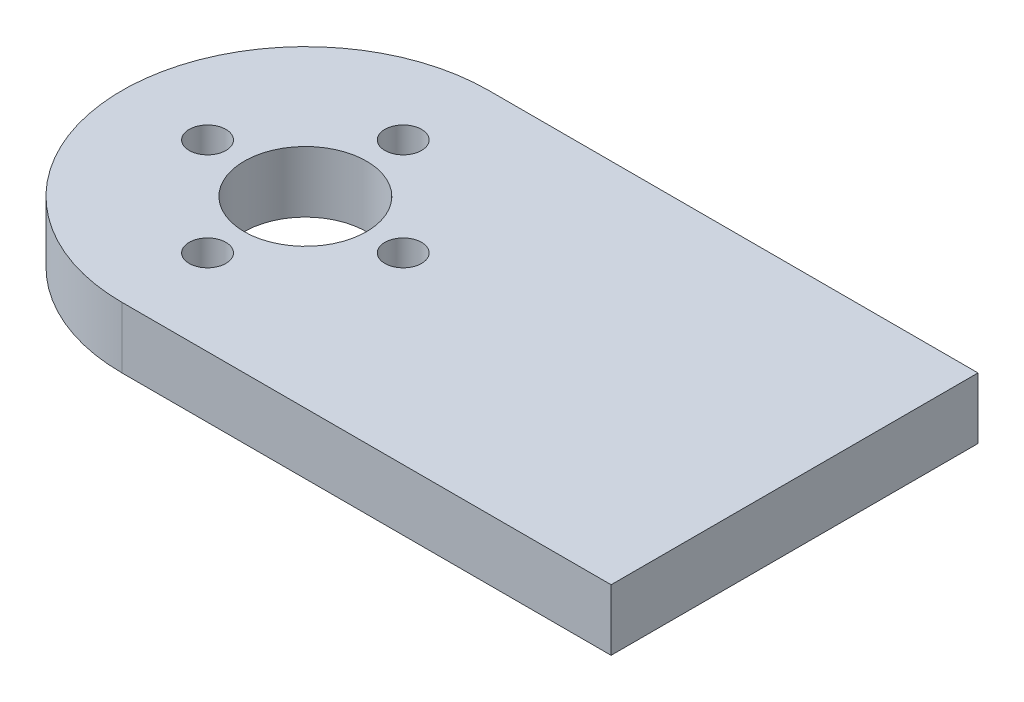
SolidWorks part; units mm, degrees
ref_plane "Front Plane" through (0, 0, 0) normal (0, 0, 1) x (1, 0, 0)
ref_plane "Top Plane" through (0, 0, 0) normal (0, 1, 0) x (1, 0, 0)
ref_plane "Right Plane" through (0, 0, 0) normal (1, 0, 0) x (0, 0, -1)
sketch "Sketch1" plane through (0, 0, 0) normal (0, 1, 0) x (1, 0, 0)
  line L0 (0, 0) -> (0, 8)
  line L2 (0, 15) -> (40, 15)
  line L3 (0, 15) -> (0, -15)
  line L4 (0, -15) -> (40, -15)
  line L5 (40, 15) -> (40, -15)
  circle A0 centre (0, 0) radius 5
  circle A1 centre (0, 0) radius 15
  circle A2 centre (0, 0) radius 8
  circle A3 centre (0, 8) radius 1.5
  circle A4 centre (8, 0) radius 1.5
  circle A5 centre (0, -8) radius 1.5
  circle A6 centre (-8, 0) radius 1.5
  dimension "D1" = 10
  dimension "D2" = 30
  dimension "D3" = 16
  dimension "D4" = 3
  dimension "D6" = 16
  dimension "D7" = 30
  dimension "D8" = 40
  dimension "D5" = 4
extrude "Boss-Extrude1" add sketch "Sketch1" along normal blind 5 contours A6 A2 A3 L3 A1 A5 | A5 L3 A1 A3 A2 A4 | A6 A2 A5 L3 A0 A3 | A5 A2 A4 A3 L3 A0 | A1 L4 L5 L2
